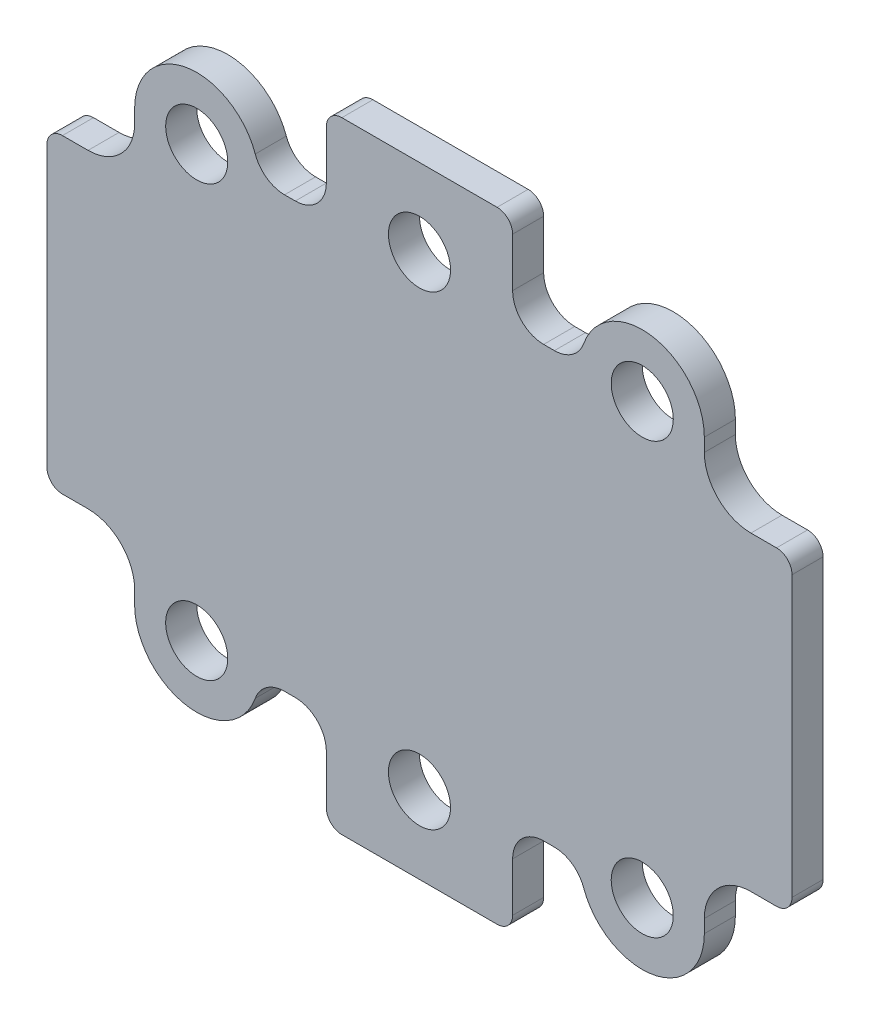
SolidWorks part; units mm, degrees
ref_plane "正面" through (0, 0, 0) normal (0, 0, 1) x (1, 0, 0)
ref_plane "平面" through (0, 0, 0) normal (0, 1, 0) x (1, 0, 0)
ref_plane "右側面" through (0, 0, 0) normal (1, 0, 0) x (0, 0, -1)
sketch "ｽｹｯﾁ1" plane through (0, 0, 0) normal (0, 0, 1) x (1, 0, 0)
  line L0 (0, 0) -> (12, 0)
  line L1 (12, 0) -> (12, -4.15)
  line L4 (24.35, -6.15) -> (24.35, -10)
  line L5 (24.35, -10) -> (30, -10)
  line L6 (30, -10) -> (30, -30)
  line L7 (30, -20) -> (6, -20) construction
  line L8 (6, 0) -> (6, -20) construction
  line L9 (24.35, -30) -> (30, -30)
  line L10 (24.35, -33.85) -> (24.35, -30)
  line L13 (12, -40) -> (12, -35.85)
  line L14 (0, -40) -> (12, -40)
  line L15 (-12.35, -30) -> (-18, -30)
  line L16 (-18, -10) -> (-18, -30)
  line L17 (-12.35, -10) -> (-18, -10)
  line L18 (0, -40) -> (0, -35.85)
  line L21 (-12.35, -33.85) -> (-12.35, -30)
  line L22 (-12.35, -6.15) -> (-12.35, -10)
  line L25 (0, 0) -> (0, -4.15)
  line L26 (14, -6.15) -> (14.6931, -6.15)
  line L27 (-2, -6.15) -> (-2.6931, -6.15)
  line L28 (14, -33.85) -> (14.6931, -33.85)
  line L29 (-2, -33.85) -> (-2.6931, -33.85)
  arc A0 (16.5788, -4.8167) -> (24.35, -6.15) centre (20.35, -6.15) cw
  arc A1 (16.5788, -35.1833) -> (24.35, -33.85) centre (20.35, -33.85) ccw
  arc A2 (-4.5788, -35.1833) -> (-12.35, -33.85) centre (-8.35, -33.85) cw
  arc A3 (-4.5788, -4.8167) -> (-12.35, -6.15) centre (-8.35, -6.15) ccw
  arc A4 (12, -4.15) -> (14, -6.15) centre (14, -4.15) ccw
  arc A5 (14.6931, -6.15) -> (16.5788, -4.8167) centre (14.6931, -4.15) ccw
  arc A6 (14.6931, -33.85) -> (16.5788, -35.1833) centre (14.6931, -35.85) cw
  arc A7 (12, -35.85) -> (14, -33.85) centre (14, -35.85) cw
  arc A8 (0, -35.85) -> (-2, -33.85) centre (-2, -35.85) ccw
  arc A9 (-2.6931, -33.85) -> (-4.5788, -35.1833) centre (-2.6931, -35.85) ccw
  arc A10 (-2.6931, -6.15) -> (-4.5788, -4.8167) centre (-2.6931, -4.15) cw
  arc A11 (0, -4.15) -> (-2, -6.15) centre (-2, -4.15) cw
  circle A12 centre (20.35, -6.15) radius 2
  circle A13 centre (-8.35, -6.15) radius 2
  circle A14 centre (20.35, -33.85) radius 2
  circle A15 centre (-8.35, -33.85) radius 2
  circle A16 centre (6, -5) radius 2
  circle A17 centre (6, -35) radius 2
  point P37 (12, -6.15)
  point P40 (16.35, -6.15)
  dimension "D4" = 4
  dimension "D8" = 2
  dimension "D9" = 4
  dimension "D10" = 5
  dimension "D11" = 4
  dimension "D1" = 27.7
  dimension "D2" = 28.7
  dimension "D3" = 12
  dimension "D5" = 40
  dimension "D6" = 20
  dimension "D7" = 48
extrude "ﾎﾞｽ - 押し出し1" add sketch "ｽｹｯﾁ1" along normal blind 2
fillet "ﾌｨﾚｯﾄ1" radius 3 4 edges at (-12.35, -30, 1) (24.35, -30, 1) (24.35, -10, 1) (-12.35, -10, 1)
fillet "ﾌｨﾚｯﾄ2" radius 1 8 edges at (30, -30, 1) (30, -10, 1) (-18, -30, 1) (-18, -10, 1) (0, -40, 1) (12, -40, 1) (12, 0, 1) (0, 0, 1)
